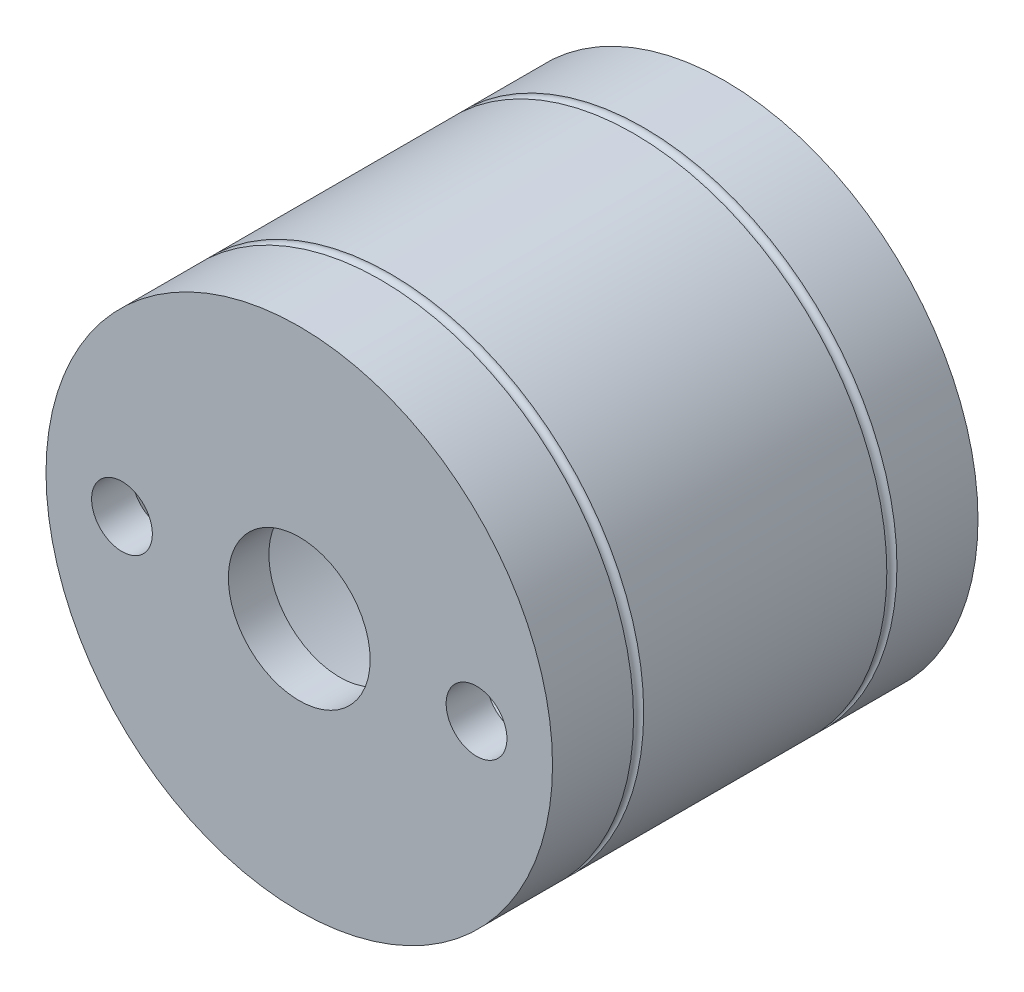
SolidWorks part; units mm, degrees
material "AISI 1010 Steel, hot rolled bar"
ref_plane "Alzado" through (0, 0, 0) normal (0, 0, 1) x (1, 0, 0)
ref_plane "Planta" through (0, 0, 0) normal (0, 1, 0) x (1, 0, 0)
ref_plane "Vista lateral" through (0, 0, 0) normal (1, 0, 0) x (0, 0, -1)
sketch "Sketch1" plane through (0, 0, 0) normal (0, 0, 1) x (1, 0, 0)
  circle A0 centre (0, 0) radius 12.5
  dimension "D1" = 25
extrude "Boss-Extrude1" add sketch "Sketch1" along normal blind 21
shell "Shell1" thickness 2
sketch "Sketch3" plane through (0, 0, 21) normal (0, 0, 1) x (1, 0, 0)
  circle A0 centre (0, 0) radius 3.5
  dimension "D1" = 7
extrude "Cut-Extrude1" cut sketch "Sketch3" against normal through all
sketch "Sketch4" plane through (0, 0, 21) normal (0, 0, 1) x (1, 0, 0)
  line L0 (-12.5, 0) -> (12.5, 0) construction
  line L1 (0, 12.5) -> (0, -12.5) construction
  circle A0 centre (8.75, 0) radius 1.5
  circle A1 centre (0, 0) radius 12.5 construction
  circle A2 centre (-8.75, 0) radius 1.5
  dimension "D1" = 3
  dimension "D2" = 8.75
extrude "Cut-Extrude2" cut sketch "Sketch4" against normal through all
ref_plane "Plane1" through (0, 0, 4.25) normal (0, 0, -1) x (-1, 0, 0)
ref_plane "Plane2" through (0, 0, 16.75) normal (0, 0, 1) x (1, 0, 0)
sketch "Sketch6" plane through (0, 0, 16.75) normal (0, 0, 1) x (1, 0, 0)
  circle A0 centre (0, 0) radius 12.5
sketch "Sketch7" plane through (0, 0, 4.25) normal (0, 0, -1) x (-1, 0, 0)
  circle A0 centre (0, 0) radius 12.5
sketch "Sketch8" plane through (0, 0, 0) normal (1, 0, 0) x (0, 0, -1)
  line L0 (0, 12.5) -> (-21, 12.5) construction
  line L1 (-4.25, -13.75) -> (-4.25, 13.75) construction
  circle A0 centre (-4.25, 12.5) radius 0.25
  dimension "D1" = 0.5
sketch "Sketch9" plane through (0, 0, 0) normal (1, 0, 0) x (0, 0, -1)
  line L1 (-16.75, 13.75) -> (-16.75, -13.75) construction
  circle A0 centre (-16.75, 12.5) radius 0.25
  circle A1 centre (-4.25, 12.5) radius 0.25 construction
sweep "Cut-Sweep1" cut profiles "Sketch9" path "Sketch6"
sweep "Cut-Sweep2" cut profiles "Sketch8" path "Sketch7"
